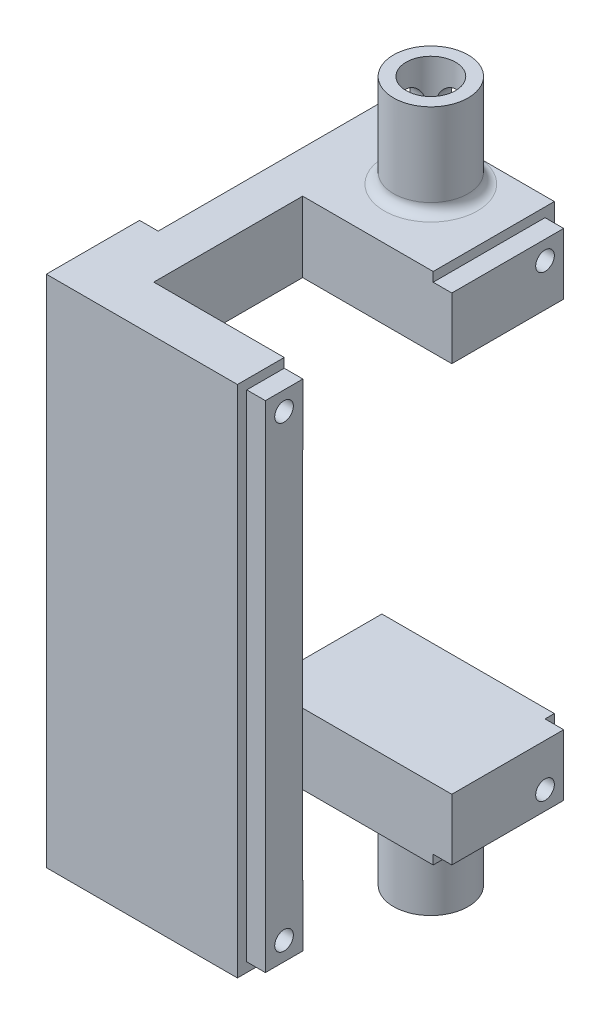
SolidWorks part; units mm, degrees
ref_plane "前视基准面" through (0, 0, 0) normal (0, 0, 1) x (1, 0, 0)
ref_plane "上视基准面" through (0, 0, 0) normal (0, 1, 0) x (1, 0, 0)
ref_plane "右视基准面" through (0, 0, 0) normal (1, 0, 0) x (0, 0, -1)
other "Configuration Table"
sketch "草图1" plane through (0, 0, 0) normal (0, 0, 1) x (1, 0, 0)
  line L0 (-1000, 0) -> (49000, 0) construction
  line L1 (-10.25, -20) -> (10.25, -20)
  line L2 (-10.25, -20) -> (-10.25, 20)
  line L3 (-10.25, 20) -> (10.25, 20)
  line L4 (10.25, -20) -> (10.25, 20)
  line L5 (-10.25, -20) -> (10.25, 20) construction
  line L6 (-10.25, 20) -> (10.25, -20) construction
  line L7 (-5, 15) -> (5, 15)
  line L8 (-5, 15) -> (-5, 25)
  line L9 (-5, 25) -> (5, 25)
  line L10 (5, 15) -> (5, 25)
  line L11 (-5, 15) -> (5, 25) construction
  line L12 (-5, 25) -> (5, 15) construction
  line L14 (-10.25, -35.1417) -> (10.25, -35.1417)
  line L15 (-10.25, -35.1417) -> (-10.25, 35.1417)
  line L16 (-10.25, 35.1417) -> (10.25, 35.1417)
  line L17 (10.25, -35.1417) -> (10.25, 35.1417)
  line L18 (-10.25, -35.1417) -> (10.25, 35.1417) construction
  line L19 (-10.25, 35.1417) -> (10.25, -35.1417) construction
  circle A0 centre (-5, 25) radius 2
  circle A1 centre (5, 25) radius 2
  circle A2 centre (5, -25) radius 2
  circle A3 centre (-5, -25) radius 2
  point P0 (0, 0)
  point P6 (0, 20)
  point P19 (0, 0)
  dimension "D5" = 4
  dimension "D6" = 4
  dimension "D1" = 20.5
  dimension "D2" = 40
  dimension "D3" = 10
  dimension "D4" = 10
extrude "凸台-拉伸1" add sketch "草图1" along normal blind 29 contours A1 L10 L3 L17 L16 L15 L8 A0 L9 | L14 L17 L1 L15 A2 A3 | A1 L9 A0 L8 L3 L10
sketch "草图2" plane through (0, 0, 29) normal (0, 0, 1) x (1, 0, 0)
  line L1 (-10.25, 35.1417) -> (10.25, 35.1417)
  line L2 (-10.25, 35.1417) -> (-10.25, -35.1417)
  line L3 (-10.25, -35.1417) -> (10.25, -35.1417)
  line L4 (10.25, 35.1417) -> (10.25, -35.1417)
extrude "凸台-拉伸2" add sketch "草图2" along normal blind 3
sketch "草图3" plane through (0, 0, 0) normal (0, 0, -1) x (-1, 0, 0)
  line L0 (-10.25, -35.1417) -> (-10.25, -20) construction
  line L1 (-10.25, -27.5709) -> (10.25, -27.5709)
  line L2 (-10.25, -27.5709) -> (-10.25, 27.5709)
  line L3 (-10.25, 27.5709) -> (10.25, 27.5709)
  line L4 (10.25, -27.5709) -> (10.25, 27.5709)
  line L5 (10.25, 20) -> (10.25, 35.1417) construction
  line L7 (-10.25, -35.1417) -> (10.25, -35.1417)
  line L8 (-10.25, -35.1417) -> (-10.25, 35.1417)
  line L9 (-10.25, 35.1417) -> (10.25, 35.1417)
  line L10 (10.25, -35.1417) -> (10.25, 35.1417)
  line M2 (-10.25, -35.1417) -> (10.25, -35.1417)
  line M3 (10.25, -35.1417) -> (10.25, -20)
  line M5 (-10.25, -20) -> (-10.25, -35.1417)
extrude "切除-拉伸1" cut sketch "草图3" against normal through all contours L1 M5 M2 M3 | L3 L10 L9 L8
sketch "草图5" plane through (0, -27.5709, 0) normal (0, -1, 0) x (1, 0, 0)
  line L0 (0, 0) -> (0, 2.5)
  circle A0 centre (0, 2.5) radius 2.5
  dimension "D2" = 5
  dimension "D1" = 2.5
extrude "凸台-拉伸3" add sketch "草图5" along normal blind 10
sketch "草图8" plane through (0, 27.5709, 0) normal (0, 1, 0) x (1, 0, 0)
  line L0 (0, 0) -> (0, -2.5)
  line L1 (0, -2.5) -> (0, -16.5)
  line L2 (0, -16.5) -> (0, -26.5)
  circle A0 centre (0, -16.5) radius 1.6
  circle A1 centre (0, -26.5) radius 1.6
  dimension "D4" = 3.2
  dimension "D5" = 3.2
  dimension "D1" = 2.5
  dimension "D2" = 14
  dimension "D3" = 10
extrude "切除-拉伸2" cut sketch "草图8" against normal up to next
sketch "草图9" plane through (0, -27.5709, 0) normal (0, -1, 0) x (1, 0, 0)
  line L1 (-10.25, 32) -> (10.25, 32)
  line L2 (-10.25, 32) -> (-10.25, 0)
  line L3 (-10.25, 0) -> (10.25, 0)
  line L4 (10.25, 32) -> (10.25, 0)
extrude "切除-拉伸3" cut sketch "草图9" along normal through all
sketch "草图12" plane through (0, 0, 0) normal (0, 0, -1) x (-1, 0, 0)
  line L1 (-10.25, 27.5709) -> (10.25, 27.5709)
  line L2 (-10.25, 27.5709) -> (-10.25, 20)
  line L3 (-10.25, 20) -> (10.25, 20)
  line L4 (10.25, 27.5709) -> (10.25, 20)
  circle A0 centre (-5, 25) radius 2
  circle A1 centre (5, 25) radius 2
extrude "凸台-拉伸5" add sketch "草图12" against normal blind 30
sketch "草图13" plane through (0, 27.5709, 0) normal (0, 1, 0) x (1, 0, 0)
  line L0 (0, 0) -> (0, -32)
  line L1 (10.25, -32) -> (-10.25, -32) construction
  line L2 (0, 0) -> (0, -10)
  line L3 (0, 0) -> (0, -2.5275)
  line L4 (0, 0) -> (0, -5)
  circle A2 centre (0, -5) radius 2.5
  circle A3 centre (0, -5) radius 4
  dimension "D3" = 5
  dimension "D4" = 5
  dimension "D5" = 8
  dimension "D1" = 32
  dimension "D2" = 10
extrude "凸台-拉伸6" add sketch "草图13" along normal blind 10 contours L4 A3 L2 A2 | L2 A3 L4 A2
sketch "草图15" plane through (0, 0, 0) normal (1, 0, 0) x (0, 0, -1)
  line L0 (-1, 27.5709) -> (0, 27.5709)
  line L1 (-1, 27.5709) -> (-1, 28.676)
  line L2 (-1, 27.5709) -> (-1, 37.5709) construction
  line L3 (-5, -962.4291) -> (-5, 49037.5709) construction
  line L4 (-2.5, 37.5709) -> (-7.5, 37.5709) construction
  arc A0 (-1, 28.676) -> (0, 27.5709) centre (0.1107, 28.676) ccw
  point P13 (-5, 37.5709)
revolve "旋转1" add sketch "草图15" angle 360 about L3
ref_plane "基准面1" through (0, 0, 5) normal (0, 0, 1) x (1, 0, 0)
sketch "草图16" plane through (0, 0, 5) normal (0, 0, 1) x (1, 0, 0)
  line L0 (0, 37.5709) -> (0, 33.5709)
  line L1 (2.5, 37.5709) -> (-2.5, 37.5709) construction
  circle A0 centre (0, 33.5709) radius 1.5
  dimension "D2" = 3
  dimension "D1" = 4
extrude "切除-拉伸5" cut sketch "草图16" against normal through all
sketch "草图17" plane through (0, 0, 0) normal (1, 0, 0) x (0, 0, -1)
  line L0 (-5, 37.5709) -> (-5, 33.5709)
  line L1 (-2.5, 37.5709) -> (-7.5, 37.5709) construction
  line L2 (-5, 11.275) -> (-5, -11.275) construction
  circle A0 centre (-5, 33.5709) radius 1.5
  dimension "D2" = 3
  dimension "D1" = 4
extrude "切除-拉伸6" cut sketch "草图17" against normal through all
sketch "草图19" plane through (0, -27.5709, 0) normal (0, -1, 0) x (1, 0, 0)
  line L0 (0, 0) -> (0, 5)
  line L1 (10.25, 0) -> (-10.25, 0) construction
  circle A0 centre (0, 5) radius 2.5
  circle A1 centre (0, 5) radius 4
  dimension "D2" = 5
  dimension "D3" = 8
  dimension "D1" = 5
extrude "凸台-拉伸7" add sketch "草图19" along normal blind 10
sketch "草图20" plane through (0, 0, 0) normal (1, 0, 0) x (0, 0, -1)
  line L0 (-1, -27.5709) -> (0, -27.5709)
  line L1 (-1, -27.5709) -> (-1, -28.5709)
  line L2 (-1, -37.5709) -> (-1, -27.5709) construction
  line L3 (-5, -1027.5709) -> (-5, 48972.4291) construction
  line L4 (-9, -27.5709) -> (-1, -27.5709) construction
  arc A0 (-1, -28.5709) -> (0, -27.5709) centre (0, -28.5709) cw
  point P13 (-5, -27.5709)
  dimension "D1" = 1
revolve "旋转2" add sketch "草图20" angle 360 about L3
sketch "草图21" plane through (0, 0, 5) normal (0, 0, 1) x (1, 0, 0)
  line L0 (0, -37.5709) -> (0, -33.5709)
  line L1 (-4, -37.5709) -> (4, -37.5709) construction
  circle A0 centre (0, -33.5709) radius 1.5
  dimension "D2" = 3
  dimension "D1" = 4
extrude "切除-拉伸7" cut sketch "草图21" against normal through all
sketch "草图22" plane through (0, 0, 0) normal (1, 0, 0) x (0, 0, -1)
  line L0 (-5, -37.5709) -> (-5, -33.5709)
  line L1 (-9, -37.5709) -> (-1, -37.5709) construction
  line L2 (-5, 11.275) -> (-5, -11.275) construction
  circle A0 centre (-5, -33.5709) radius 1.5
  dimension "D2" = 3
  dimension "D1" = 4
extrude "切除-拉伸8" cut sketch "草图22" against normal through all
sketch "草图23" plane through (0, 0, 32) normal (0, 0, 1) x (1, 0, 0)
  line L1 (-10.25, 27.5709) -> (10.25, 27.5709)
  line L2 (-10.25, 27.5709) -> (-10.25, -27.5709)
  line L3 (-10.25, -27.5709) -> (10.25, -27.5709)
  line L4 (10.25, 27.5709) -> (10.25, -27.5709)
extrude "凸台-拉伸8" add sketch "草图23" along normal blind 2
sketch "草图24" plane through (-10.25, 0, 0) normal (-1, 0, 0) x (0, 0, 1)
  line L0 (34, -27.5709) -> (0, -27.5709) construction
  line L1 (34, 27.5709) -> (24, 27.5709)
  line L2 (34, 27.5709) -> (34, -27.5709)
  line L3 (34, -27.5709) -> (24, -27.5709)
  line L4 (24, 27.5709) -> (24, -27.5709)
  dimension "D1" = 10
extrude "凸台-拉伸9" add sketch "草图24" along normal blind 2
sketch "草图25" plane through (10.25, 0, 0) normal (1, 0, 0) x (0, 0, -1)
  line L0 (-34, 27.5709) -> (-21, 27.5709)
  line L1 (-34, 27.5709) -> (0, 27.5709) construction
  line L2 (-21, 27.5709) -> (-17, 27.5709)
  line L3 (-17, 27.5709) -> (-17, -27.5709)
  line L6 (-17, -27.5709) -> (-25, -27.5709)
  line L7 (-34, -27.5709) -> (0, -27.5709) construction
  line L8 (-25, -27.5709) -> (-25, 27.5709)
  line M5 (-29, 20) -> (0, 20)
  line M7 (0, 27.5709) -> (-34, 27.5709)
  line M9 (-34, -27.5709) -> (0, -27.5709)
  line M11 (0, -20) -> (-29, -20)
  dimension "D1" = 13
  dimension "D2" = 4
  dimension "D3" = 8
extrude "切除-拉伸9" cut sketch "草图25" against normal blind 16 contours L8 L3 M9 M11 | L8 L3 M5 M7
sketch "草图26" plane through (0, 0, 29) normal (0, 0, -1) x (-1, 0, 0)
  circle A0 centre (-5, 25) radius 2
  circle A1 centre (5, 25) radius 2
  circle A2 centre (-5, -25) radius 2
  circle A3 centre (5, -25) radius 2
extrude "凸台-拉伸10" add sketch "草图26" along normal blind 20
sketch "草图27" plane through (0, -27.5709, 0) normal (0, -1, 0) x (1, 0, 0)
  line L1 (-5.75, 25) -> (10.25, 25)
  line L2 (-5.75, 25) -> (-5.75, 17)
  line L3 (-5.75, 17) -> (10.25, 17)
  line L4 (10.25, 25) -> (10.25, 17)
extrude "切除-拉伸10" cut sketch "草图27" against normal through all
sketch "草图29" plane through (10.25, 0, 0) normal (1, 0, 0) x (0, 0, -1)
  line L0 (-33, 26.5709) -> (-33, -26.5709)
  line L1 (-34, 27.5709) -> (0, 27.5709)
  line L2 (-34, 27.5709) -> (-34, -27.5709)
  line L3 (-34, -27.5709) -> (0, -27.5709)
  line L4 (0, 27.5709) -> (0, -27.5709)
  line L5 (-33, -26.5709) -> (-1, -26.5709)
  line L6 (-1, 26.5709) -> (-1, -26.5709)
  line L7 (-33, 26.5709) -> (-1, 26.5709)
  dimension "D1" = 1
extrude "切除-拉伸11" cut sketch "草图29" against normal blind 2
sketch "草图30" plane through (10.25, 0, 0) normal (1, 0, 0) x (0, 0, -1)
  line L1 (-34, 27.5709) -> (0, 27.5709)
  line L2 (-34, 27.5709) -> (-34, -27.5709)
  line L3 (-34, -27.5709) -> (0, -27.5709)
  line L4 (0, 27.5709) -> (0, -27.5709)
  dimension "D1" = 34
  dimension "D2" = 55.1417
sketch "草图32" plane through (10.25, 0, 0) normal (1, 0, 0) x (0, 0, -1)
  line L0 (-17, -26.5709) -> (-1, -26.5709) construction
  line L1 (-33, 26.5709) -> (-13, 26.5709)
  line L2 (-33, 26.5709) -> (-33, -26.5709)
  line L3 (-33, -26.5709) -> (-13, -26.5709)
  line L4 (-13, 26.5709) -> (-13, -26.5709)
  line L6 (-13, 26.5709) -> (-28.9769, 26.5709)
  line L7 (-13, 26.5709) -> (-13, -26.5709)
  line L8 (-13, -26.5709) -> (-28.9769, -26.5709)
  line L9 (-28.9769, 26.5709) -> (-28.9769, -26.5709)
  line L10 (-13, -26.5709) -> (-28.9769, -26.5709)
  line L11 (-13, -26.5709) -> (-13, 27.5939)
  line L12 (-13, 27.5939) -> (-28.9769, 27.5939)
  line L13 (-28.9769, -26.5709) -> (-28.9769, 27.5939)
  line L14 (-28.9769, 27.5939) -> (-13, 27.5939)
  line L15 (-28.9769, 27.5939) -> (-28.9769, -27.5919)
  line L16 (-28.9769, -27.5919) -> (-13, -27.5919)
  line L17 (-13, 27.5939) -> (-13, -27.5919)
  line M2 (-25, 26.5709) -> (-33, 26.5709)
  line M5 (-25, -26.5709) -> (-25, -20)
  line M6 (-25, -20) -> (-29, -20)
  line M8 (-29, 20) -> (-25, 20)
  line M9 (-25, 20) -> (-25, 26.5709)
  dimension "D1" = 20
extrude "切除-拉伸13" cut sketch "草图32" against normal blind 16 contours L9 L3 L4 L1 M8 M6 M5 M9 | L9 M2 M8 M9 | L9 L3 M6 M5 | L17 L3 L15 L16 | L13 L1 L11 L12 M2
sketch "草图33" plane through (10.25, 0, 0) normal (1, 0, 0) x (0, 0, -1)
  line L1 (-33, 26.5709) -> (-31, 26.5709)
  line L2 (-33, 26.5709) -> (-33, 24.5709)
  line L3 (-33, 24.5709) -> (-31, 24.5709)
  line L4 (-31, 26.5709) -> (-31, 24.5709)
  line L5 (-33, -26.5709) -> (-31, -26.5709)
  line L6 (-33, -26.5709) -> (-33, -24.5709)
  line L7 (-33, -24.5709) -> (-31, -24.5709)
  line L8 (-31, -26.5709) -> (-31, -24.5709)
  circle A0 centre (-31, 24.5709) radius 1
  circle A1 centre (-31, -24.5709) radius 1
  dimension "D3" = 2
  dimension "D6" = 2
  dimension "D1" = 2
  dimension "D2" = 2
  dimension "D4" = 2
  dimension "D5" = 2
extrude "切除-拉伸14" cut sketch "草图33" against normal blind 16 contours A1 | A0
sketch "草图35" plane through (10.25, 0, 0) normal (1, 0, 0) x (0, 0, -1)
  line L1 (-1, 26.5709) -> (-3, 26.5709)
  line L2 (-1, 26.5709) -> (-1, 24.5709)
  line L3 (-1, 24.5709) -> (-3, 24.5709)
  line L4 (-3, 26.5709) -> (-3, 24.5709)
  line L5 (-1, -26.5709) -> (-3, -26.5709)
  line L6 (-1, -26.5709) -> (-1, -24.5709)
  line L7 (-1, -24.5709) -> (-3, -24.5709)
  line L8 (-3, -26.5709) -> (-3, -24.5709)
  circle A0 centre (-3, 24.5709) radius 1
  circle A1 centre (-3, -24.5709) radius 1
  dimension "D3" = 2
  dimension "D6" = 2
  dimension "D1" = 2
  dimension "D2" = 2
  dimension "D4" = 2
  dimension "D5" = 2
extrude "切除-拉伸15" cut sketch "草图35" against normal blind 5 contours A1 | A0
sketch "草图36" plane through (0, -37.5709, 0) normal (0, -1, 0) x (1, 0, 0)
  circle A1 centre (0, 5) radius 2.65
  dimension "D1" = 5.3
extrude "切除-拉伸16" cut sketch "草图36" against normal blind 10
sketch "草图37" plane through (0, 37.5709, 0) normal (0, 1, 0) x (1, 0, 0)
  circle A0 centre (0, -5) radius 2.65
  dimension "D1" = 5.3
extrude "切除-拉伸17" cut sketch "草图37" against normal blind 10
